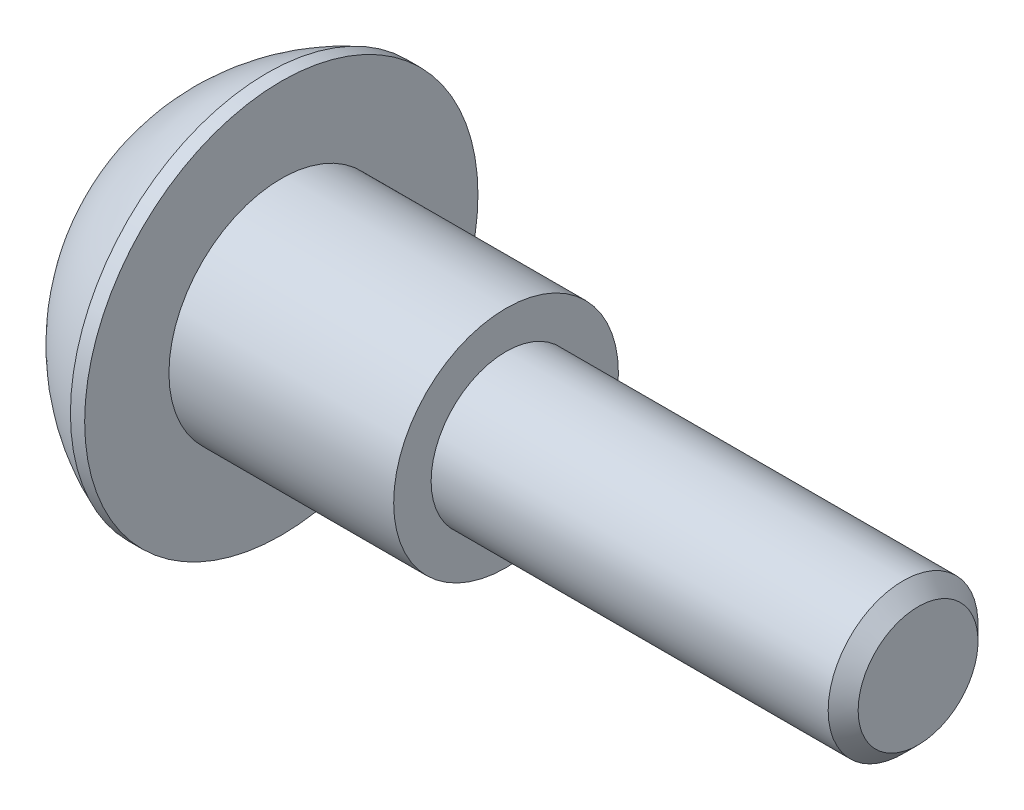
SolidWorks part; units mm, degrees
ref_plane "Plane1" through (0, 0, 0) normal (0, 0, 1) x (1, 0, 0)
ref_plane "Plane2" through (0, 0, 0) normal (0, 1, 0) x (1, 0, 0)
ref_plane "Plane3" through (0, 0, 0) normal (1, 0, 0) x (0, 0, -1)
sketch "BodySke" plane through (0, 0, 0) normal (0, 0, 1) x (1, 0, 0)
  line L0 (20.3, 0) -> (20.3, 1.6)
  line L1 (19.9, 2) -> (3.3, 2)
  line L2 (3.3, 2) -> (3.3, 5.25)
  line L3 (3.3, 5.25) -> (2.92, 5.25)
  line L4 (0, 0) -> (101.6, 0) construction
  line L5 (3.3, -5.25) -> (2.92, -5.25) construction
  line L6 (55.6768, -2) -> (3.3, -2) construction
  line L7 (20.3, 0) -> (0, 0)
  line L8 (0, 2.625) -> (0, -2.625) construction
  line L9 (0, 0) -> (0, 2.625)
  line L10 (20.3, 1.6) -> (19.9, 2)
  line L11 (20.3, -1.6) -> (19.9, -2) construction
  line L12 (4.3, 9.525) -> (4.3, -2) construction
  line L13 (0.3, 9.525) -> (0.3, -2) construction
  arc A1 (0, 2.625) -> (2.92, 5.25) centre (4.9997, 0) cw
  dimension "D2" = 45
  dimension "D1" = 5.25
  dimension "Diameter" = 4
  dimension "Length" = 17
  dimension "Head_dia" = 10.5
  dimension "Head_ht" = 3.3
  dimension "Head_side_ht" = 0.38
  dimension "Minor_dia" = 3.2
  dimension "Advance" = 1
  dimension "Thread_nom" = 20
revolve "BaseBody" add sketch "BodySke" angle 360 about L4
cosmetic thread "ThreadCosmetic" parameters "Thread_length"=13, "Thread_minor"=3.2
fillet "Fillet1" radius 0.01 1 edges at (3.3, 0, 2)
sketch "Sketch2" plane through (0, 0, 0) normal (0, 0, 1) x (1, 0, 0)
  line L0 (0, 2) -> (2.08, 2)
  line L1 (2.08, 2) -> (3.2347, 0)
  line L3 (3.2347, 0) -> (0, 0)
  line L4 (0, 0) -> (0, 2)
  line L5 (0, -2) -> (2.08, -2) construction
  line L6 (0, 0) -> (47.625, 0) construction
  dimension "D2" = 60
  dimension "PreBroach_depth" = 2.08
  dimension "PreBroach_dia" = 4
revolve "PreBroach" cut sketch "Sketch2" angle 360 about L6
sketch "Sketch3" plane through (0, 0, 0) normal (1, 0, 0) x (0, 0, -1)
  line L0 (-2, -1.1547) -> (-2, 1.1547)
  line L1 (-2, 1.1547) -> (0, 2.3094)
  line L2 (0, 2.3094) -> (2, 1.1547)
  line L3 (2, 1.1547) -> (2, -1.1547)
  line L4 (2, -1.1547) -> (0, -2.3094)
  line L5 (0, -2.3094) -> (-2, -1.1547)
  dimension "D1" = 2
  dimension "D2" = 2
  dimension "D3" = 4
  dimension "Hex_size" = 4
extrude "Hex" cut sketch "Sketch3" along normal blind 2.08
sketch "Esboço1" plane through (3.3, 0, 0) normal (1, 0, 0) x (0, 0, -1)
  circle A0 centre (0, 0) radius 3
  dimension "D1" = 6
extrude "Ressalto-extrusão1" add sketch "Esboço1" along normal blind 6
